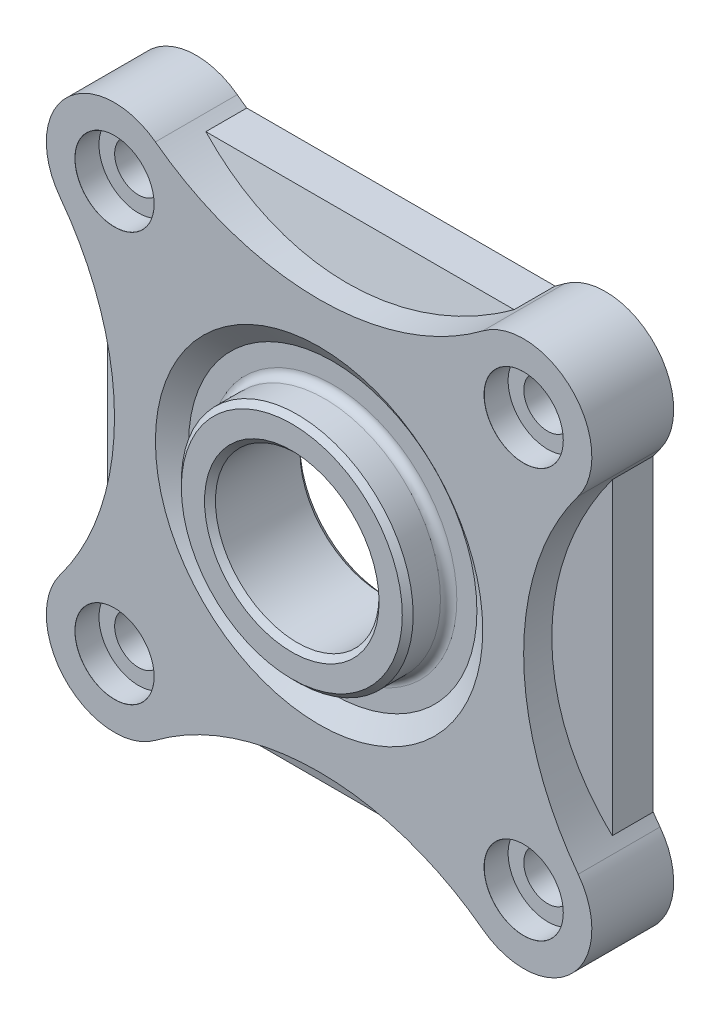
SolidWorks part; units mm, degrees
material "ASTM A36 Steel"
ref_plane "Front Plane" through (0, 0, 0) normal (0, 0, 1) x (1, 0, 0)
ref_plane "Top Plane" through (0, 0, 0) normal (0, 1, 0) x (1, 0, 0)
ref_plane "Right Plane" through (0, 0, 0) normal (1, 0, 0) x (0, 0, -1)
sketch "Sketch1" plane through (0, 0, 0) normal (0, 0, 1) x (1, 0, 0)
  line L1 (-75, -75) -> (75, -75) construction
  line L2 (-75, -75) -> (-75, 75) construction
  line L3 (-75, 75) -> (75, 75) construction
  line L4 (75, -75) -> (75, 75) construction
  line L5 (-75, -75) -> (75, 75) construction
  line L6 (-75, 75) -> (75, -75) construction
  circle A0 centre (-75, 75) radius 25
  circle A1 centre (75, 75) radius 25
  circle A2 centre (-75, -75) radius 25
  circle A3 centre (75, -75) radius 25
  arc A4 (-95, -60) -> (-95, 60) centre (-175, 0) ccw
  arc A5 (-60, 95) -> (60, 95) centre (0, 175) ccw
  arc A6 (95, 60) -> (95, -60) centre (175, 0) ccw
  arc A7 (60, -95) -> (-60, -95) centre (0, -175) ccw
  point P0 (0, 0)
  dimension "D3" = 50
  dimension "D4" = 100
  dimension "D1" = 150
  dimension "D2" = 150
extrude "Boss-Extrude1" add sketch "Sketch1" along normal blind 30 contours A7 A3 A6 A1 A5 A0 A4 A2 | A0 | A1 | A3 | A2
sketch "Sketch2" plane through (0, 0, 0) normal (0, 0, 1) x (1, 0, 0)
  line L1 (-92.5, -92.5) -> (92.5, -92.5)
  line L2 (-92.5, -92.5) -> (-92.5, 92.5)
  line L3 (-92.5, 92.5) -> (92.5, 92.5)
  line L4 (92.5, -92.5) -> (92.5, 92.5)
  line L5 (-92.5, -92.5) -> (92.5, 92.5) construction
  line L6 (-92.5, 92.5) -> (92.5, -92.5) construction
  point P0 (0, 0)
  dimension "D1" = 185
extrude "Boss-Extrude2" add sketch "Sketch2" along normal blind 15
draft "Draft1" type of draft neutral plane draft angle 15 faces to draft 1 face at (83.75, 0, 15) neutral plane through (92.5, -92.5, 15) neutral plane normal (1, 0, 0) parameters "D1"=15
draft "Draft2" type of draft neutral plane draft angle 15 faces to draft 1 face at (0, 83.75, 15) neutral plane through (-92.5, 92.5, 15) neutral plane normal (0, 1, 0) parameters "D1"=15
draft "Draft3" type of draft neutral plane draft angle 15 faces to draft 1 face at (-83.75, 0, 15) neutral plane through (-92.5, -92.5, 15) neutral plane normal (-1, 0, 0) parameters "D1"=15
draft "Draft4" type of draft neutral plane draft angle 15 faces to draft 1 face at (0, -83.75, 15) neutral plane through (-92.5, -92.5, 15) neutral plane normal (0, -1, 0) parameters "D1"=15
sketch "Sketch3" plane through (0, 0, 0) normal (0, 0, 1) x (1, 0, 0)
  circle A0 centre (0, 0) radius 42.5
  dimension "D1" = 85
extrude "Boss-Extrude3" add sketch "Sketch3" along normal blind 40
sketch "Sketch4" plane through (0, 0, 30) normal (0, 0, 1) x (1, 0, 0)
  point P0 (-75, 75)
  point P3 (75, 75)
  point P6 (-75, -75)
  point P9 (75, -75)
hole_wizard "CBORE for M16 SBHCS1" positions "Sketch4" profile "Sketch5" counterbore size "M16" standard "ANSI Metric" end condition through all
sketch "Sketch5" plane through (-75, 75, 30) normal (1, 0, 0) x (0, -1, 0)
  line L0 (0, 0) -> (0, 30)
  line L1 (0, 30) -> (8.75, 30)
  line L3 (8.75, 30) -> (8.75, 8.8)
  line L4 (14.5, 8.8) -> (8.75, 8.8)
  line L5 (14.5, 8.8) -> (14.5, 0.025)
  line L6 (14.5, 0.025) -> (14.525, 0)
  line L7 (14.525, 0) -> (0, 0)
  line L8 (-14.5, 0.025) -> (-14.525, 0) construction
  line L11 (0, -6.35) -> (0, 107.95) construction
  dimension "Thru Hole Dia." = 17.5
  dimension "Thru Hole Depth" = 30
  dimension "C'Bore Dia." = 29
  dimension "C'Bore Depth" = 8.8
  dimension "Near C'Sink Dia." = 29.05
  dimension "Near C'Sink Angle" = 90
sketch "Sketch6" plane through (0, 0, 40) normal (0, 0, 1) x (1, 0, 0)
  circle A0 centre (0, 0) radius 30
  dimension "D1" = 60
extrude "Cut-Extrude1" cut sketch "Sketch6" against normal through all
sketch "Sketch7" plane through (0, 0, 0) normal (0, 0, -1) x (-1, 0, 0)
  circle A0 centre (0, 0) radius 77.5
  dimension "D1" = 155
extrude "Cut-Extrude2" cut sketch "Sketch7" against normal blind 5
sketch "Sketch8" plane through (0, 0, 0) normal (1, 0, 0) x (0, 0, -1)
  line L0 (-77.4041, 0) -> (39.4789, 0) construction
  line L1 (-30, 42.5) -> (-30, 60)
  line L2 (-30, 60) -> (-30, -60) construction
  line L3 (-30, 60) -> (-25, 52.8593)
  line L4 (-25, 52.8593) -> (-25, 42.5)
  line L5 (-25, 42.5) -> (-30, 42.5)
  dimension "D1" = 120
  dimension "D2" = 5
  dimension "D3" = 35
revolve "Cut-Revolve1" cut sketch "Sketch8" angle 360 about L0
fillet "Fillet1" radius 3 1 edges at (42.5, 0, 25)
chamfer "Chamfer1" distance 2 angle 45 3 edges at (-30, 0, 5) (30, 0, 40) (42.5, 0, 40)
